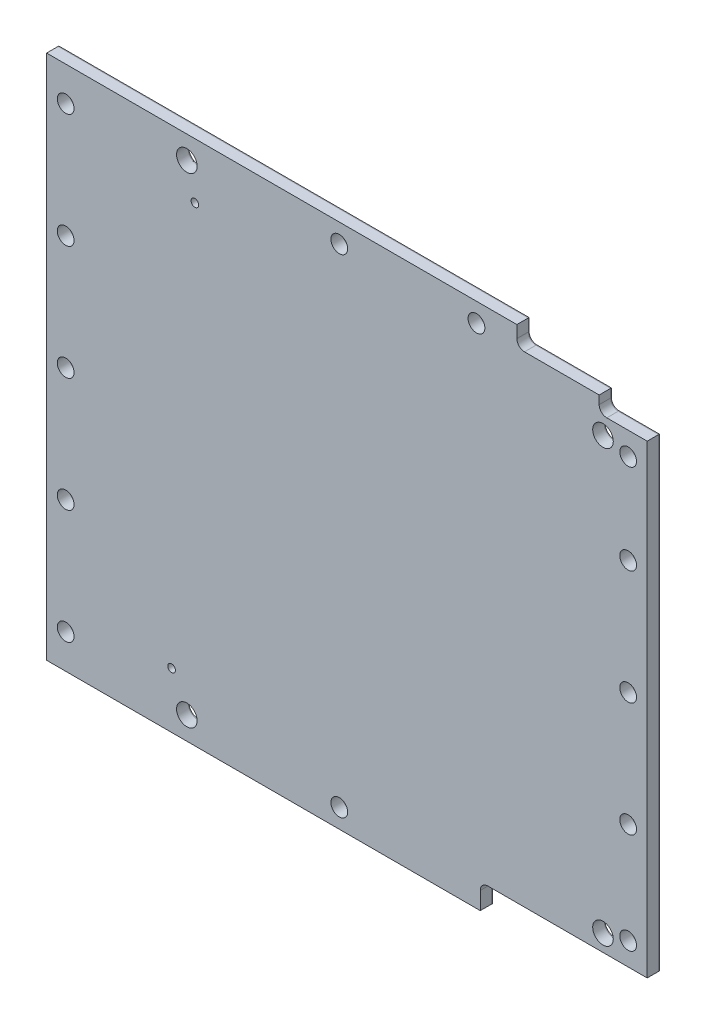
SolidWorks part; units mm, degrees
ref_plane "Front Plane" through (0, 0, 0) normal (0, 0, 1) x (1, 0, 0)
ref_plane "Top Plane" through (0, 0, 0) normal (0, 1, 0) x (1, 0, 0)
ref_plane "Right Plane" through (0, 0, 0) normal (1, 0, 0) x (0, 0, -1)
sketch "Sketch1" plane through (0, 0, 0) normal (0, 0, 1) x (1, 0, 0)
  line L0 (39.5, 0.3) -> (60.4, 0.3)
  line L1 (60.4, 0.3) -> (60.4, 61.3)
  line L2 (60.4, 61.3) -> (55.1, 61.3)
  line L3 (54.1, 62.3) -> (54.1, 63.4)
  line L4 (54.1, 63.4) -> (44.3, 63.4)
  line L5 (43.3, 64.4) -> (43.3, 66)
  line L6 (43.3, 66) -> (-18.4, 66)
  line L7 (-18.4, 66) -> (-18.4, -3)
  line L8 (-18.4, -3) -> (38.5, -3)
  line L9 (38.5, -3) -> (38.5, -0.7)
  circle A2 centre (0, 0) radius 1.35 construction
  circle A6 centre (20, -0.5) radius 1.1
  arc A17 (55.1, 61.3) -> (54.1, 62.3) centre (55.1, 62.3) cw
  arc A18 (44.3, 63.4) -> (43.3, 64.4) centre (44.3, 64.4) cw
  arc A19 (38.5, -0.7) -> (39.5, 0.3) centre (39.5, -0.7) cw
  dimension "D3" = 1
  dimension "D4" = 20
  dimension "D6" = 38.5
  dimension "D7" = 43.3
  dimension "D8" = 54.1
  dimension "D11" = 60.4
  dimension "D13" = 18.4
  dimension "D14" = 0.3
  dimension "D22" = 61.3
  dimension "D25" = 63.4
  dimension "D27" = 66
  dimension "D28" = 0.5
  dimension "D29" = 3
extrude "BASE EXTRUDE" add sketch "Sketch1" against normal blind 1.6
hole_wizard "M2 MTG" positions "3DSketch1" profile "Sketch3" hole size "M2" standard "Ansi Metric"
sketch3d "3DSketch1"
  circle A13 centre (0, 0, 0) radius 1.5406
  point P4 (-15.9, 31.5, 0)
  point P7 (-15.9, 16.5, 0)
  point P9 (-15.9, 1.5, 0)
  point P11 (-15.9, 46.5, 0)
  point P13 (-15.9, 61.5, 0)
  point P15 (20, 63.5, 0)
  point P17 (38, 63.5, 0)
  point P19 (57.9, 58.3, 0)
  point P21 (57.9, 46.5, 0)
  point P23 (57.9, 31.5, 0)
  point P25 (57.9, 16.5, 0)
  point P27 (57.9, 3.3, 0)
  point P29 (20, -0.5, 0)
  point P102 (0, 0, 1.5406)
  dimension "D5" = 15
  dimension "D1" = 15
  dimension "D2" = 15
  dimension "D3" = 15
  dimension "D4" = 15
  dimension "D6" = 15
  dimension "D7" = 11.8
  dimension "D8" = 15
  dimension "D9" = 13.2
  dimension "D10" = 6.3
  dimension "D11" = 2.5
  dimension "D12" = 2.5
  dimension "D13" = 38.4
  dimension "D14" = 2.5
sketch "Sketch3" plane through (-15.9, 31.5, 0) normal (1, 0, 0) x (0, -1, 0)
  line L0 (0, 0) -> (0, 2.2609)
  line L1 (0, 2.2609) -> (1.1, 1.6)
  line L2 (1.1, 1.6) -> (1.1, 0)
  line L5 (1.1, 0) -> (0, 0)
  line L10 (0, 2.2609) -> (-1.1, 1.6) construction
  line L11 (0, -6.35) -> (0, 107.95) construction
  dimension "Hole Dia." = 2.2
  dimension "Hole Depth" = 1.6
  dimension "Drill Angle" = 118
hole_wizard "M2.5 Clearance Hole1" positions "3DSketch2" profile "Sketch4" hole size "M2.5" standard "Ansi Metric"
sketch3d "3DSketch2"
  point P0 (54.6, 2.5, 0)
  point P2 (0, 0, 0)
  point P4 (0, 63, 0)
  point P6 (54.6, 59.05, 0)
  dimension "D1" = 5.5
  dimension "D2" = 5.8
  dimension "D3" = 6.95
  dimension "D4" = 3
sketch "Sketch4" plane through (54.6, 2.5, 0) normal (1, 0, 0) x (0, -1, 0)
  line L0 (0, 0) -> (0, 2.4112)
  line L1 (0, 2.4112) -> (1.35, 1.6)
  line L2 (1.35, 1.6) -> (1.35, 0)
  line L5 (1.35, 0) -> (0, 0)
  line L10 (0, 2.4112) -> (-1.35, 1.6) construction
  line L11 (0, -6.35) -> (0, 107.95) construction
  dimension "Hole Dia." = 2.7
  dimension "Hole Depth" = 1.6
  dimension "Drill Angle" = 118
hole_wizard "CONNECTOR REF" positions "Sketch10" profile "Sketch9" legacy end condition through all
sketch "Sketch10" plane through (0, 0, -1.6) normal (0, 0, -1) x (-1, 0, 0)
  circle A0 centre (0, 0) radius 1.35 construction
  point P0 (2, 4.3)
  point P2 (-1.05, 58.7)
  dimension "D1" = 4.3
  dimension "D2" = 2
  dimension "D3" = 58.7
  dimension "D4" = 1.05
sketch "Sketch9" plane through (-2, 4.3, -1.6) normal (1, 0, 0) x (0, 1, 0)
  line L0 (0, 0) -> (0, 1.6)
  line L1 (0, 1.6) -> (0.5, 1.6)
  line L2 (0.5, 1.6) -> (0.5, 0)
  line L3 (0.5, 0) -> (0, 0)
  line L4 (0, 110) -> (0, -10) construction
  dimension "Diameter" = 1
  dimension "Depth" = 1.6
sketch "KEEPOUT" plane through (0, 0, -1.6) normal (0, 0, -1) x (-1, 0, 0)
  line L0 (-39.5, 0.3) -> (-60.4, 0.3) construction
  line L2 (-60.4, 61.3) -> (-55.4, 61.3)
  line L4 (-60.4, 61.3) -> (-60.4, 0.3)
  line L6 (-60.4, 0.3) -> (-55.4, 0.3)
  line L8 (-55.4, 61.3) -> (-55.4, 0.3)
  line L9 (18.4, -3) -> (-38.5, -3) construction
  line L16 (18.4, 66) -> (13.4, 66)
  line L17 (18.4, 66) -> (18.4, -3)
  line L18 (18.4, -3) -> (13.4, -3)
  line L19 (13.4, 66) -> (13.4, -3)
  dimension "D1" = 5
  dimension "D2" = 5
sketch "KEEPOUT OPT" plane through (0, 0, -1.6) normal (0, 0, -1) x (-1, 0, 0)
  line L0 (13.4, 61) -> (-52.4, 61)
  line L1 (13.4, 66) -> (13.4, -3) construction
  line L2 (-43.3, 66) -> (18.4, 66) construction
  line L3 (13.4, 61) -> (13.4, 66)
  line L4 (13.4, 66) -> (-43.3, 66)
  line L5 (-43.3, 64.4) -> (-43.3, 66) construction
  line L6 (-54.1, 63.4) -> (-44.3, 63.4) construction
  line L7 (-54.1, 62.3) -> (-54.1, 63.4) construction
  line L8 (-43.3, 64.4) -> (-43.3, 66)
  line L9 (-54.1, 63.4) -> (-44.3, 63.4)
  line L10 (-54.1, 62.3) -> (-54.1, 63.4)
  line L11 (-55.1, 61.3) -> (-55.4, 61.3)
  line L12 (-55.4, 61.3) -> (-55.4, 56.8)
  line L13 (-55.4, 61.3) -> (-55.4, 0.3) construction
  line L14 (-55.4, 56.8) -> (-52.4, 56.8)
  line L15 (-52.4, 56.8) -> (-52.4, 61)
  line L16 (-38.5, -3) -> (-38.5, -0.7) construction
  line L17 (13.4, -3) -> (-38.5, -3)
  line L18 (13.4, -3) -> (13.4, 2)
  line L19 (13.4, 2) -> (-52.4, 2)
  line L20 (-56.326, 0.3) -> (-56.326, 4.75)
  line L21 (-39.5, 0.3) -> (-60.4, 0.3) construction
  line L22 (-38.5, -3) -> (-38.5, -0.7)
  line L23 (-39.5, 0.3) -> (-56.326, 0.3)
  line L25 (-52.4, 4.75) -> (-56.326, 4.75)
  line L26 (-52.4, 4.75) -> (-52.4, 2)
  arc A0 (-44.3, 63.4) -> (-43.3, 64.4) centre (-44.3, 64.4) ccw construction
  arc A1 (-55.1, 61.3) -> (-54.1, 62.3) centre (-55.1, 62.3) ccw construction
  arc A2 (-44.3, 63.4) -> (-43.3, 64.4) centre (-44.3, 64.4) ccw
  arc A3 (-55.1, 61.3) -> (-54.1, 62.3) centre (-55.1, 62.3) ccw
  arc A4 (-38.5, -0.7) -> (-39.5, 0.3) centre (-39.5, -0.7) ccw construction
  arc A5 (-38.5, -0.7) -> (-39.5, 0.3) centre (-39.5, -0.7) ccw
  circle A6 centre (-54.6, 2.5) radius 1.35 construction
  dimension "D5" = 2.25
  dimension "D1" = 5
  dimension "D2" = 56.8
  dimension "D3" = 52.4
  dimension "D4" = 5
  dimension "D6" = 2.2
sketch "IO AREA" plane through (0, 0, -1.6) normal (0, 0, -1) x (-1, 0, 0)
  line L0 (-60.4, 61.3) -> (-60.4, 0.3) construction
  line L1 (-60.4, 55.8) -> (-34.6, 55.8)
  line L2 (-60.4, 55.8) -> (-60.4, 5.8)
  line L3 (-60.4, 5.8) -> (-34.6, 5.8)
  line L4 (-34.6, 55.8) -> (-34.6, 5.8)
  circle A0 centre (0, 0) radius 1.35 construction
  dimension "D3" = 5.8
  dimension "D1" = 25.8
  dimension "D2" = 50
extrude "Cut-Extrude1" cut sketch "KEEPOUT" against normal blind 0.1
sketch "Sketch11" plane through (0, 0, -1.5) normal (0, 0, -1) x (-1, 0, 0)
  line L0 (-55.4, 60.1374) -> (-55.4, 61.3) construction
  line L1 (-55.4, 61.3) -> (-60.4, 61.3) construction
  line L2 (-60.4, 61.3) -> (-60.4, 0.3) construction
  line L3 (-60.4, 0.3) -> (-55.4, 0.3) construction
  line L4 (-55.4, 0.3) -> (-55.4, 1.4126) construction
  line L5 (-55.4, 3.5874) -> (-55.4, 57.9626) construction
  line L6 (18.4, -3) -> (18.4, 66) construction
  line L7 (18.4, 66) -> (13.4, 66) construction
  line L8 (13.4, 66) -> (13.4, -3) construction
  line L9 (13.4, -3) -> (18.4, -3) construction
  line L10 (-55.4, 60.1374) -> (-55.4, 61.3)
  line L11 (-55.4, 61.3) -> (-60.4, 61.3)
  line L12 (-60.4, 61.3) -> (-60.4, 0.3)
  line L13 (-60.4, 0.3) -> (-55.4, 0.3)
  line L14 (-55.4, 0.3) -> (-55.4, 1.4126)
  line L15 (-55.4, 3.5874) -> (-55.4, 57.9626)
  line L16 (18.4, -3) -> (18.4, 66)
  line L17 (18.4, 66) -> (13.4, 66)
  line L18 (13.4, 66) -> (13.4, -3)
  line L19 (13.4, -3) -> (18.4, -3)
  arc A0 (-55.4, 60.1374) -> (-55.4, 57.9626) centre (-54.6, 59.05) ccw construction
  arc A1 (-55.4, 3.5874) -> (-55.4, 1.4126) centre (-54.6, 2.5) ccw construction
  arc A2 (-55.4, 60.1374) -> (-55.4, 57.9626) centre (-54.6, 59.05) ccw
  arc A3 (-55.4, 3.5874) -> (-55.4, 1.4126) centre (-54.6, 2.5) ccw
  circle A4 centre (-57.9, 58.3) radius 1.1 construction
  circle A5 centre (-57.9, 46.5) radius 1.1 construction
  circle A6 centre (-57.9, 31.5) radius 1.1 construction
  circle A7 centre (-57.9, 16.5) radius 1.1 construction
  circle A8 centre (-57.9, 3.3) radius 1.1 construction
  circle A9 centre (15.9, 1.5) radius 1.1 construction
  circle A10 centre (15.9, 16.5) radius 1.1 construction
  circle A11 centre (15.9, 31.5) radius 1.1 construction
  circle A12 centre (15.9, 46.5) radius 1.1 construction
  circle A13 centre (15.9, 61.5) radius 1.1 construction
  circle A14 centre (-57.9, 58.3) radius 1.1
  circle A15 centre (-57.9, 46.5) radius 1.1
  circle A16 centre (-57.9, 31.5) radius 1.1
  circle A17 centre (-57.9, 16.5) radius 1.1
  circle A18 centre (-57.9, 3.3) radius 1.1
  circle A19 centre (15.9, 1.5) radius 1.1
  circle A20 centre (15.9, 16.5) radius 1.1
  circle A21 centre (15.9, 31.5) radius 1.1
  circle A22 centre (15.9, 46.5) radius 1.1
  circle A23 centre (15.9, 61.5) radius 1.1
extrude "Boss-Extrude1" add sketch "Sketch11" along normal up to surface (0.1 mm away) separate body up to face at (41.8458, 36.7584, -1.6)
extrude "Cut-Extrude2" cut sketch "KEEPOUT OPT" against normal blind 0.1
sketch "Sketch12" plane through (0, 0, -1.5) normal (0, 0, -1) x (-1, 0, 0)
  line L0 (-55.4, 61.3) -> (-55.4, 60.1374)
  line L1 (-55.4, 57.9626) -> (-55.4, 56.8)
  line L2 (-52.4, 2) -> (-52.4, 4.75)
  line L3 (-52.4, 2) -> (13.4, 2)
  line L4 (13.4, 2) -> (13.4, -3)
  line L5 (13.4, 66) -> (13.4, 61)
  line L6 (-55.4, 56.8) -> (-52.4, 56.8)
  line L7 (-52.4, 4.75) -> (-55.4, 4.75)
  line L8 (-52.4, 61) -> (13.4, 61)
  line L9 (-55.4, 4.75) -> (-55.4, 3.5874)
  line L10 (-55.1, 61.3) -> (-60.4, 61.3)
  line L11 (-60.4, 61.3) -> (-60.4, 0.3)
  line L12 (-60.4, 0.3) -> (-39.5, 0.3)
  line L13 (-38.5, -0.7) -> (-38.5, -3)
  line L14 (-38.5, -3) -> (18.4, -3)
  line L15 (18.4, -3) -> (18.4, 66)
  line L16 (18.4, 66) -> (-43.3, 66)
  line L17 (-43.3, 66) -> (-43.3, 64.4)
  line L18 (-44.3, 63.4) -> (-54.1, 63.4)
  line L19 (-54.1, 63.4) -> (-54.1, 62.3)
  line L20 (-55.1, 61.3) -> (-55.4, 61.3)
  line L21 (-55.4, 1.4126) -> (-55.4, 0.3)
  line L22 (-55.4, 0.3) -> (-39.5, 0.3)
  line L23 (-38.5, -0.7) -> (-38.5, -3)
  line L24 (-38.5, -3) -> (13.4, -3)
  line L25 (-52.4, 56.8) -> (-52.4, 61)
  line L26 (13.4, 66) -> (-43.3, 66)
  line L27 (-43.3, 66) -> (-43.3, 64.4)
  line L28 (-44.3, 63.4) -> (-54.1, 63.4)
  line L29 (-54.1, 63.4) -> (-54.1, 62.3)
  circle A0 centre (-54.6, 59.05) radius 1.35 construction
  circle A1 centre (-38, 63.5) radius 1.1 construction
  circle A2 centre (-20, 63.5) radius 1.1 construction
  arc A3 (-55.1, 61.3) -> (-54.1, 62.3) centre (-55.1, 62.3) ccw
  arc A4 (-38.5, -0.7) -> (-39.5, 0.3) centre (-39.5, -0.7) ccw
  arc A5 (-44.3, 63.4) -> (-43.3, 64.4) centre (-44.3, 64.4) ccw
  arc A6 (-55.1, 61.3) -> (-54.1, 62.3) centre (-55.1, 62.3) ccw
  arc A7 (-38.5, -0.7) -> (-39.5, 0.3) centre (-39.5, -0.7) ccw
  arc A8 (-44.3, 63.4) -> (-43.3, 64.4) centre (-44.3, 64.4) ccw
  circle A9 centre (0, 63) radius 1.35 construction
  circle A11 centre (-54.6, 2.5) radius 1.35 construction
  circle A12 centre (-20, -0.5) radius 1.1 construction
  circle A13 centre (0, 0) radius 1.35 construction
  arc A14 (-55.4, 57.9626) -> (-55.4, 60.1374) centre (-54.6, 59.05) ccw
  circle A15 centre (-38, 63.5) radius 1.1
  circle A16 centre (-20, 63.5) radius 1.1
  circle A17 centre (0, 63) radius 1.35
  arc A19 (-55.4, 1.4126) -> (-55.4, 3.5874) centre (-54.6, 2.5) ccw
  circle A20 centre (-20, -0.5) radius 1.1
  circle A21 centre (0, 0) radius 1.35
  dimension "D1" = 0
extrude "Boss-Extrude2" add sketch "Sketch12" along normal blind 0.1 separate body
